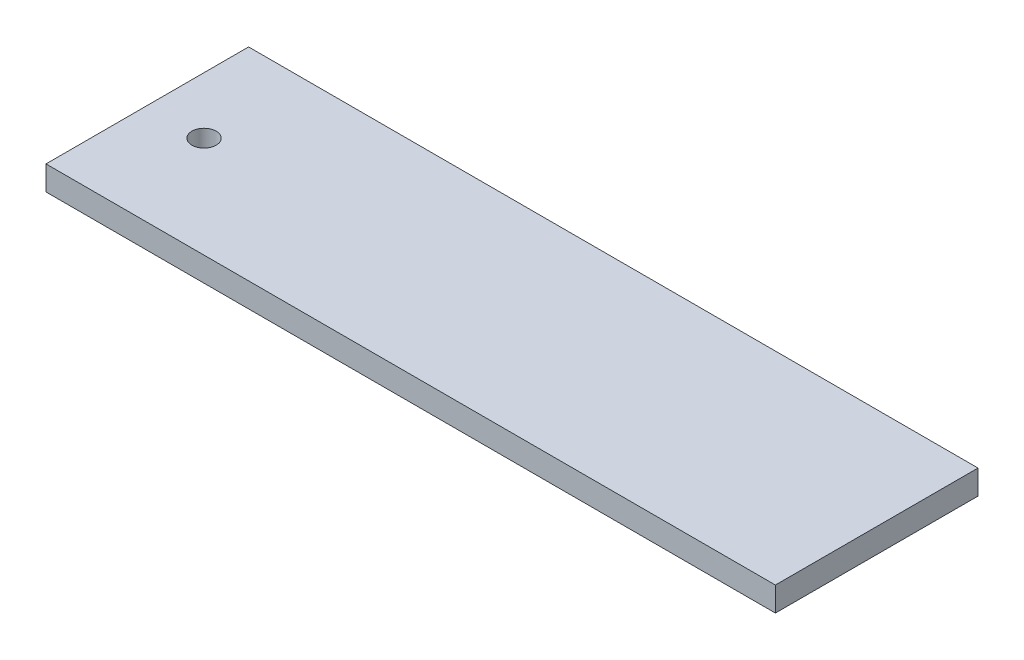
SolidWorks part; units mm, degrees
ref_plane "Front Plane" through (0, 0, 0) normal (0, 0, 1) x (1, 0, 0)
ref_plane "Top Plane" through (0, 0, 0) normal (0, 1, 0) x (1, 0, 0)
ref_plane "Right Plane" through (0, 0, 0) normal (1, 0, 0) x (0, 0, -1)
sketch "Sketch1" plane through (0, 0, 0) normal (0, 1, 0) x (1, 0, 0)
  line L1 (-45, 12.5) -> (45, 12.5)
  line L2 (-45, 12.5) -> (-45, -12.5)
  line L3 (-45, -12.5) -> (45, -12.5)
  line L4 (45, 12.5) -> (45, -12.5)
  line L5 (-45, 12.5) -> (45, -12.5) construction
  line L6 (-45, -12.5) -> (45, 12.5) construction
  point P0 (0, 0)
  dimension "D1" = 25
  dimension "D2" = 90
extrude "Boss-Extrude1" add sketch "Sketch1" along normal blind 3
sketch "Sketch2" plane through (0, 3, 0) normal (0, 1, 0) x (1, 0, 0)
  line L0 (-45, 12.5) -> (-45, -12.5) construction
  line L1 (45, 12.5) -> (-45, 12.5) construction
  circle A0 centre (-38, 0) radius 1.5
  dimension "D1" = 7
  dimension "D2" = 12.5
extrude "Cut-Extrude1" cut sketch "Sketch2" against normal blind 10
